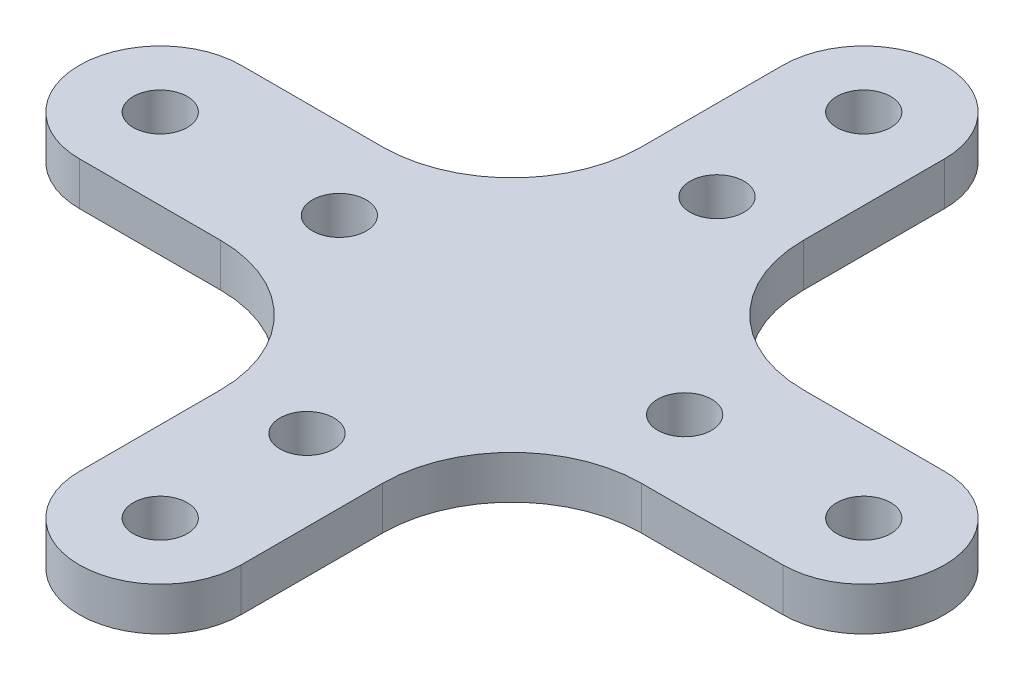
SolidWorks part; units mm, degrees
ref_plane "前基準面" through (0, 0, 0) normal (0, 0, 1) x (1, 0, 0)
ref_plane "上基準面" through (0, 0, 0) normal (0, 1, 0) x (1, 0, 0)
ref_plane "右基準面" through (0, 0, 0) normal (1, 0, 0) x (0, 0, -1)
sketch "草圖1" plane through (0, 0, 0) normal (0, 1, 0) x (1, 0, 0)
  line L0 (-3.75, 16.3) -> (-3.75, 9.75)
  line L1 (-16.3, 3.75) -> (-9.75, 3.75)
  line L2 (-16.3, -3.75) -> (-9.75, -3.75)
  line L3 (3.75, 16.3) -> (3.75, 9.75)
  line L4 (0, 16.3) -> (0, -16.3) construction
  line L5 (-16.3, 0) -> (16.3, 0) construction
  line L6 (-3.75, -9.75) -> (-3.75, -16.3)
  line L7 (9.75, -3.75) -> (16.3, -3.75)
  line L8 (3.75, -9.75) -> (3.75, -16.3)
  line L9 (9.75, 3.75) -> (16.3, 3.75)
  arc A0 (-16.3, 3.75) -> (-16.3, -3.75) centre (-16.3, 0) ccw
  arc A1 (16.3, -3.75) -> (16.3, 3.75) centre (16.3, 0) ccw
  arc A2 (3.75, 16.3) -> (-3.75, 16.3) centre (0, 16.3) ccw
  arc A3 (-3.75, -16.3) -> (3.75, -16.3) centre (0, -16.3) ccw
  circle A4 centre (0, 16.3) radius 1.25
  circle A5 centre (-16.3, 0) radius 1.25
  circle A6 centre (0, -16.3) radius 1.25
  circle A7 centre (16.3, 0) radius 1.25
  circle A8 centre (0, 9.5) radius 1.25
  circle A9 centre (-8, 0) radius 1.25
  circle A10 centre (0, -9.5) radius 1.25
  circle A11 centre (8, 0) radius 1.25
  arc A12 (-3.75, -9.75) -> (-9.75, -3.75) centre (-9.75, -9.75) ccw
  arc A13 (9.75, -3.75) -> (3.75, -9.75) centre (9.75, -9.75) ccw
  arc A14 (3.75, 9.75) -> (9.75, 3.75) centre (9.75, 9.75) ccw
  arc A15 (-3.75, 9.75) -> (-9.75, 3.75) centre (-9.75, 9.75) cw
  point P16 (0, 0)
  point P17 (0, 0)
  point P35 (3.75, -3.75)
  point P38 (3.75, 3.75)
  dimension "D1" = 7.5
  dimension "D3" = 2.5
  dimension "D4" = 2.5
  dimension "D9" = 6
  dimension "D2" = 32.6
  dimension "D5" = 9.5
  dimension "D6" = 8
  dimension "D7" = 8
  dimension "D8" = 9.5
extrude "填料-伸長1" add sketch "草圖1" along normal blind 2
